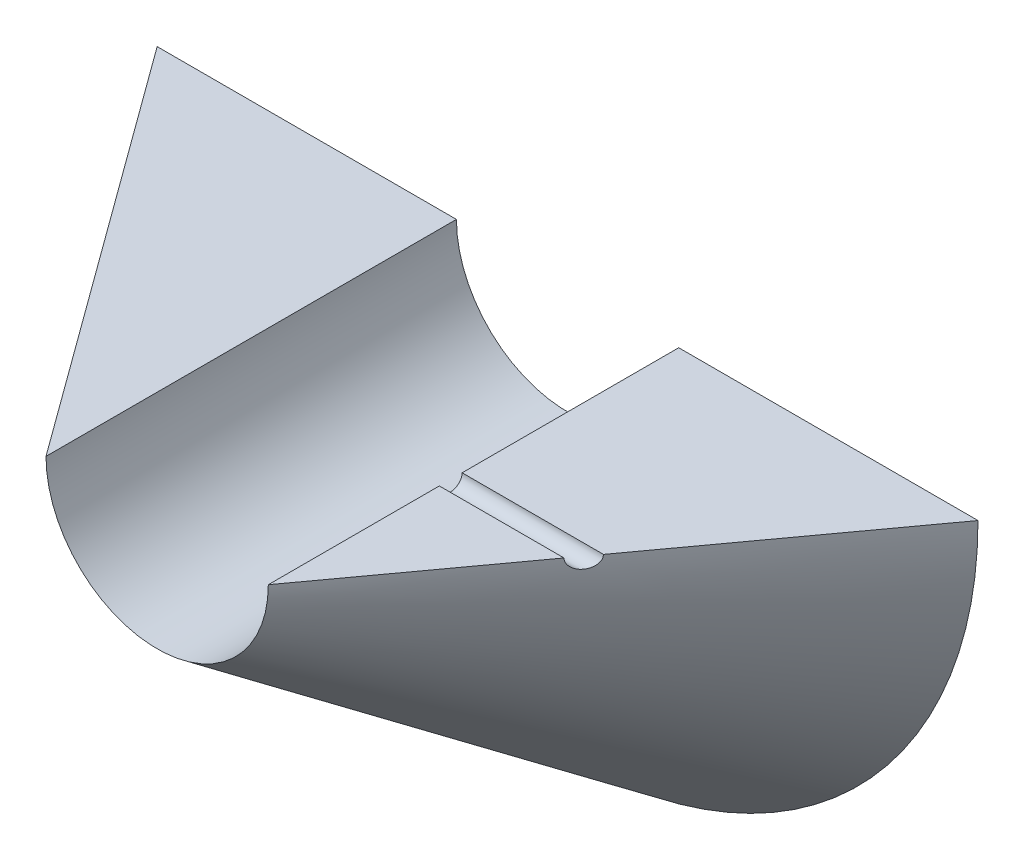
SolidWorks part; units mm, degrees
ref_plane "Plan de face" through (0, 0, 0) normal (0, 0, 1) x (1, 0, 0)
ref_plane "Plan de dessus" through (0, 0, 0) normal (0, 1, 0) x (1, 0, 0)
ref_plane "Plan de droite" through (0, 0, 0) normal (1, 0, 0) x (0, 0, -1)
sketch "Esquisse1" plane through (0, 0, 0) normal (0, 0, 1) x (1, 0, 0)
  circle A0 centre (0, 0) radius 180
  circle A1 centre (0, 0) radius 48.75
  dimension "D1" = 360
  dimension "D2" = 97.5
ref_plane "Plan1" through (0, 0, 180) normal (0, 0, 1) x (1, 0, 0)
sketch "Esquisse2" plane through (0, 0, 180) normal (0, 0, 1) x (1, 0, 0)
  circle A0 centre (0, 0) radius 48.75
  dimension "D1" = 97.5
sketch "Esquisse4" plane through (0, 0, 0) normal (1, 0, 0) x (0, 0, -1)
  line L0 (-180, 48.75) -> (0, 180)
  line L6 (-180, 48.75) -> (0, 48.75)
  line L9 (0, 48.75) -> (0, 180)
ref_axis "Axe1" through (0, 0, 180) along (0, 0, -1)
revolve "Révolution1" add sketch "Esquisse4" angle 360 about axis through (0, 0, 180) along (0, 0, -1)
ref_plane "Plan2" through (0, 0, 100) normal (0, 0, 1) x (1, 0, 0)
sketch "Esquisse6" plane through (0, 0, 100) normal (0, 0, 1) x (1, 0, 0)
  line L0 (0, 0) -> (274.7687, 64.6899)
sketch "Esquisse7" plane through (0, 0, 0) normal (1, 0, 0) x (0, 0, -1)
  circle A0 centre (-100, 0) radius 5
  dimension "D1" = 10
extrude "Enlèv. mat.-Extru.1" cut sketch "Esquisse7" along normal up to surface (110.7291 mm away) contours A0
other "Enlèv. mat.-Surface1"
